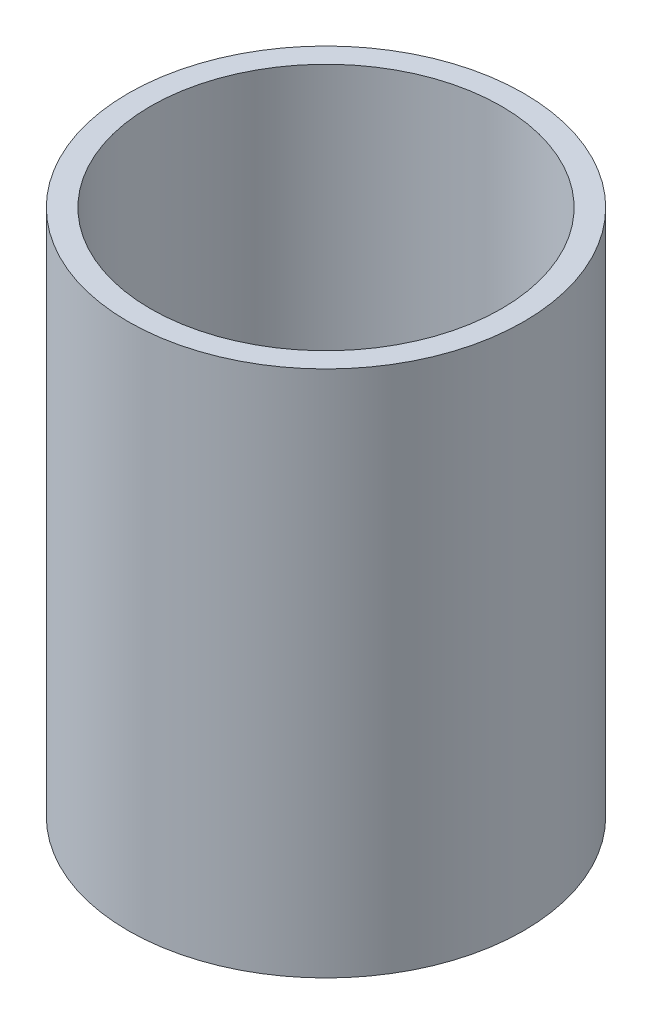
SolidWorks part; units mm, degrees
ref_plane "Front Plane" through (0, 0, 0) normal (0, 0, 1) x (1, 0, 0)
ref_plane "Top Plane" through (0, 0, 0) normal (0, 1, 0) x (1, 0, 0)
ref_plane "Right Plane" through (0, 0, 0) normal (1, 0, 0) x (0, 0, -1)
sketch "Sketch1" plane through (0, 0, 0) normal (0, 1, 0) x (1, 0, 0)
  circle A0 centre (0, 0) radius 50.7
  circle A1 centre (0, 0) radius 57.15
  dimension "D1" = 101.4
  dimension "D2" = 114.3
extrude "Boss-Extrude1" add sketch "Sketch1" along normal mid plane 152.4
